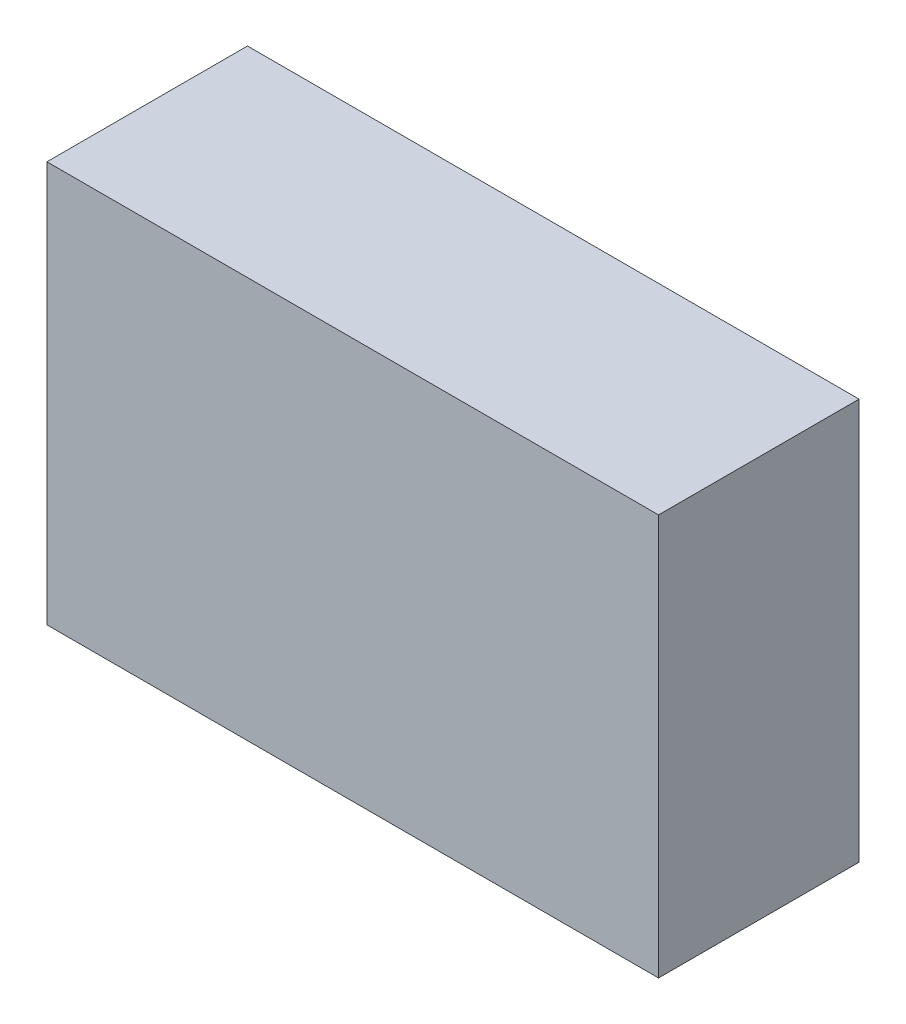
SolidWorks part; units mm, degrees
ref_plane "Front Plane" through (0, 0, 0) normal (0, 0, 1) x (1, 0, 0)
ref_plane "Top Plane" through (0, 0, 0) normal (0, 1, 0) x (1, 0, 0)
ref_plane "Right Plane" through (0, 0, 0) normal (1, 0, 0) x (0, 0, -1)
sketch "Sketch1" plane through (0, 0, 0) normal (0, 1, 0) x (1, 0, 0)
  line L1 (31.3472, -12.281) -> (-29.6528, -12.281)
  line L2 (31.3472, -12.281) -> (31.3472, 7.719)
  line L3 (31.3472, 7.719) -> (-29.6528, 7.719)
  line L4 (-29.6528, -12.281) -> (-29.6528, 7.719)
  dimension "D1" = 61
  dimension "D2" = 20
extrude "Boss-Extrude1" add sketch "Sketch1" along normal blind 40
